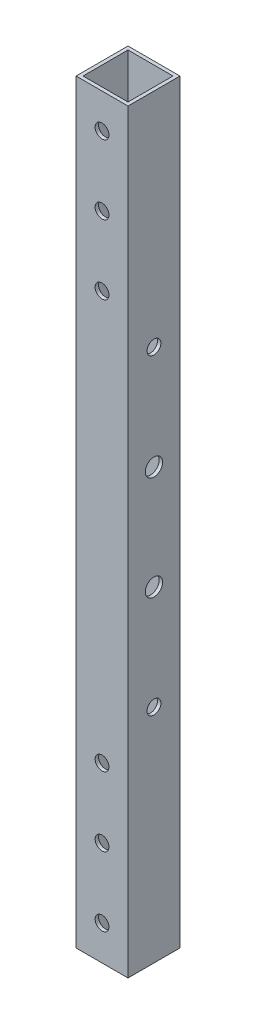
SolidWorks part; units mm, degrees
material "6061 合金"
ref_plane "Front" through (0, 0, 0) normal (0, 0, 1) x (1, 0, 0)
ref_plane "Top" through (0, 0, 0) normal (0, 1, 0) x (1, 0, 0)
ref_plane "Right" through (0, 0, 0) normal (1, 0, 0) x (0, 0, -1)
sketch "草图1" plane through (0, 0, 0) normal (0, 1, 0) x (1, 0, 0)
  line L1 (-7.5, -7.5) -> (7.5, -7.5)
  line L2 (-7.5, -7.5) -> (-7.5, 7.5)
  line L3 (-7.5, 7.5) -> (7.5, 7.5)
  line L4 (7.5, -7.5) -> (7.5, 7.5)
  line L5 (-7.5, -7.5) -> (7.5, 7.5) construction
  line L6 (-7.5, 7.5) -> (7.5, -7.5) construction
  line L7 (-6.5, -6.5) -> (6.5, -6.5)
  line L8 (-6.5, -6.5) -> (-6.5, 6.5)
  line L9 (-6.5, 6.5) -> (6.5, 6.5)
  line L10 (6.5, -6.5) -> (6.5, 6.5)
  line L11 (-6.5, -6.5) -> (6.5, 6.5) construction
  line L12 (-6.5, 6.5) -> (6.5, -6.5) construction
  point P0 (0, 0)
  point P5 (0, 0)
  dimension "D1" = 15
  dimension "D2" = 15
  dimension "D3" = 1
  dimension "D4" = 1
extrude "凸台-拉伸1" add sketch "草图1" along normal blind 218
sketch "草图3" plane through (0, 0, 7.5) normal (0, 0, 1) x (1, 0, 0)
  line L0 (0, 50) -> (0, -49950) construction
  line L1 (-7.5, 218) -> (7.5, 218) construction
  line L2 (5, 109) -> (-49995, 109) construction
  line L3 (7.5, 218) -> (7.5, 0) construction
  circle A0 centre (0, 208) radius 2
  circle A1 centre (0, 188) radius 2
  circle A2 centre (0, 30) radius 2
  circle A3 centre (0, 10) radius 2
  circle A4 centre (0, 168) radius 2
  circle A5 centre (0, 50) radius 2
  point P4 (0, 218)
  point P13 (7.5, 109)
  dimension "D1" = 4
  dimension "D2" = 4
  dimension "D5" = 4
  dimension "D3" = 20
  dimension "D4" = 10
  dimension "D6" = 20
extrude "切除-拉伸2" cut sketch "草图3" against normal through all
sketch "草图5" plane through (7.5, 0, 0) normal (1, 0, 0) x (0, 0, -1)
  line L0 (-5, 109) -> (49995, 109) construction
  line L1 (-7.5, 218) -> (-7.5, 0) construction
  line L2 (7.5, 218) -> (7.5, 0) construction
  line L3 (0, 0) -> (0, 50000) construction
  circle A1 centre (0, 124) radius 2.5
  circle A2 centre (0, 94) radius 2.5
  circle A3 centre (0, 154) radius 2
  circle A4 centre (0, 64) radius 2
  point P4 (-7.5, 109)
  point P7 (7.5, 109)
  dimension "D1" = 5
  dimension "D3" = 4
  dimension "D2" = 30
  dimension "D4" = 90
extrude "切除-拉伸4" cut sketch "草图5" against normal through all
equation "\"3。3\"=3.01309"
